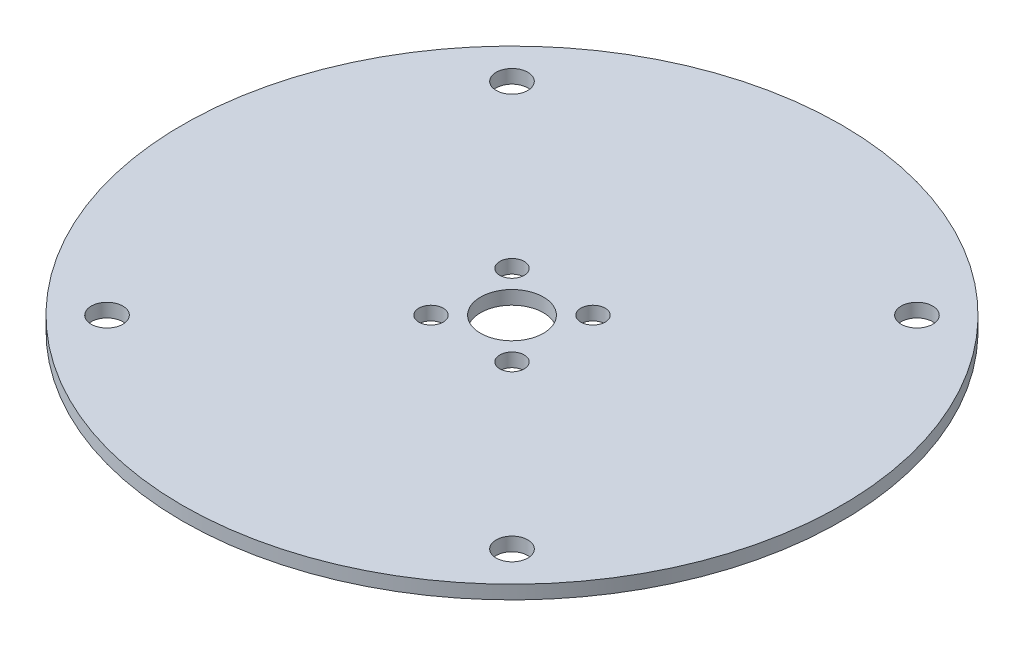
SolidWorks part; units mm, degrees
ref_plane "Front Plane" through (0, 0, 0) normal (0, 0, 1) x (1, 0, 0)
ref_plane "Top Plane" through (0, 0, 0) normal (0, 1, 0) x (1, 0, 0)
ref_plane "Right Plane" through (0, 0, 0) normal (1, 0, 0) x (0, 0, -1)
sketch "Sketch1" plane through (0, 0, 0) normal (0, 1, 0) x (1, 0, 0)
  line L1 (25, 25) -> (-25, 25) construction
  line L2 (25, 25) -> (25, -25) construction
  line L3 (25, -25) -> (-25, -25) construction
  line L4 (-25, 25) -> (-25, -25) construction
  line L5 (25, 25) -> (-25, -25) construction
  line L6 (25, -25) -> (-25, 25) construction
  line L7 (-5, 5) -> (5, 5) construction
  line L8 (-5, 5) -> (-5, -5) construction
  line L9 (-5, -5) -> (5, -5) construction
  line L10 (5, 5) -> (5, -5) construction
  line L11 (-5, 5) -> (5, -5) construction
  line L12 (-5, -5) -> (5, 5) construction
  circle A0 centre (0, 0) radius 40.69
  circle A1 centre (-25, 25) radius 1.95
  circle A2 centre (25, 25) radius 1.95
  circle A3 centre (25, -25) radius 1.95
  circle A4 centre (-25, -25) radius 1.95
  circle A5 centre (-5, 5) radius 1.5
  circle A6 centre (5, 5) radius 1.5
  circle A7 centre (5, -5) radius 1.5
  circle A8 centre (-5, -5) radius 1.5
  circle A9 centre (0, 0) radius 3.88
  dimension "D1" = 81.38
  dimension "D4" = 3.9
  dimension "D5" = 3.9
  dimension "D6" = 3.9
  dimension "D7" = 3.9
  dimension "D9" = 3
  dimension "D10" = 3
  dimension "D11" = 3
  dimension "D12" = 3
  dimension "D13" = 7.76
  dimension "D2" = 50
  dimension "D3" = 45
  dimension "D8" = 10
extrude "Boss-Extrude1" add sketch "Sketch1" along normal blind 1.68
